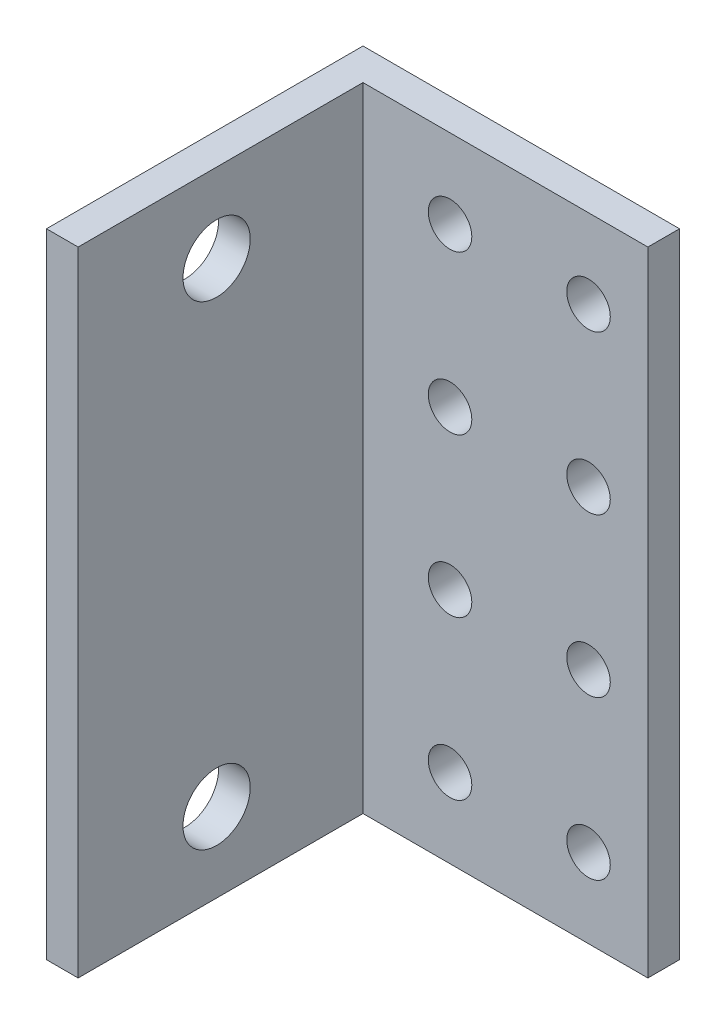
SolidWorks part; units mm, degrees
ref_plane "Front" through (0, 0, 0) normal (0, 0, 1) x (1, 0, 0)
ref_plane "Top" through (0, 0, 0) normal (0, 1, 0) x (1, 0, 0)
ref_plane "Right" through (0, 0, 0) normal (1, 0, 0) x (0, 0, -1)
sketch "Sketch1" plane through (0, 0, 0) normal (0, 1, 0) x (1, 0, 0)
  line L0 (0, 0) -> (40, 0)
  line L1 (40, 0) -> (40, -4)
  line L2 (40, -4) -> (4, -4)
  line L3 (4, -4) -> (4, -40)
  line L4 (4, -40) -> (0, -40)
  line L5 (0, -40) -> (0, 0)
  dimension "D1" = 4
  dimension "D2" = 40
extrude "Boss-Extrude1" add sketch "Sketch1" along normal blind 80
hole_wizard "Ø5.5 (5.5) Diameter Hole1" positions "Sketch2" profile "Sketch3" hole size "Ø5.5" standard "ISO"
sketch "Sketch2" plane through (0, 0, 4) normal (0, 0, 1) x (1, 0, 0)
  line L0 (15, 70) -> (32.5, 70) construction
  line L1 (32.5, 70) -> (32.5, 50) construction
  line L2 (32.5, 50) -> (32.5, 30) construction
  line L3 (32.5, 30) -> (32.5, 10) construction
  line L5 (4, 80) -> (40, 80) construction
  line L6 (40, 80) -> (40, 0) construction
  point P0 (32.5, 70)
  point P2 (15, 70)
  point P4 (15, 50)
  point P6 (32.5, 50)
  point P8 (32.5, 30)
  point P10 (15, 30)
  point P12 (15, 10)
  point P14 (32.5, 10)
  dimension "D1" = 20
  dimension "D2" = 10
  dimension "D3" = 17.5
  dimension "D4" = 7.5
sketch "Sketch3" plane through (32.5, 70, 4) normal (1, 0, 0) x (0, -1, 0)
  line L0 (0, 0) -> (0, 4)
  line L1 (0, 4) -> (2.75, 4)
  line L2 (2.75, 4) -> (2.75, 0)
  line L5 (2.75, 0) -> (0, 0)
  line L11 (0, -6.35) -> (0, 107.95) construction
  dimension "Thru Hole Dia." = 5.5
  dimension "Thru Hole Depth" = 4
hole_wizard "Ø8.5 (8.5) Diameter Hole1" positions "Sketch4" profile "Sketch5" hole size "Ø8.5" standard "ISO"
sketch "Sketch4" plane through (4, 0, 0) normal (1, 0, 0) x (0, 0, -1)
  line L0 (-22.5, 70) -> (-22.5, 10) construction
  line L2 (0, 80) -> (0, 0) construction
  line L3 (-22.5, 40) -> (-40, 40) construction
  line L4 (-40, 80) -> (-40, 0) construction
  point P0 (-22.5, 70)
  point P2 (-22.5, 10)
  dimension "D1" = 22.5
  dimension "D2" = 60
sketch "Sketch5" plane through (4, 70, 22.5) normal (0, 1, 0) x (0, 0, -1)
  line L0 (0, 0) -> (0, 4)
  line L1 (0, 4) -> (4.25, 4)
  line L2 (4.25, 4) -> (4.25, 0)
  line L5 (4.25, 0) -> (0, 0)
  line L11 (0, -6.35) -> (0, 107.95) construction
  dimension "Thru Hole Dia." = 8.5
  dimension "Thru Hole Depth" = 4
pattern_linear "LPattern1" [suppressed] count 8 spacing 82
